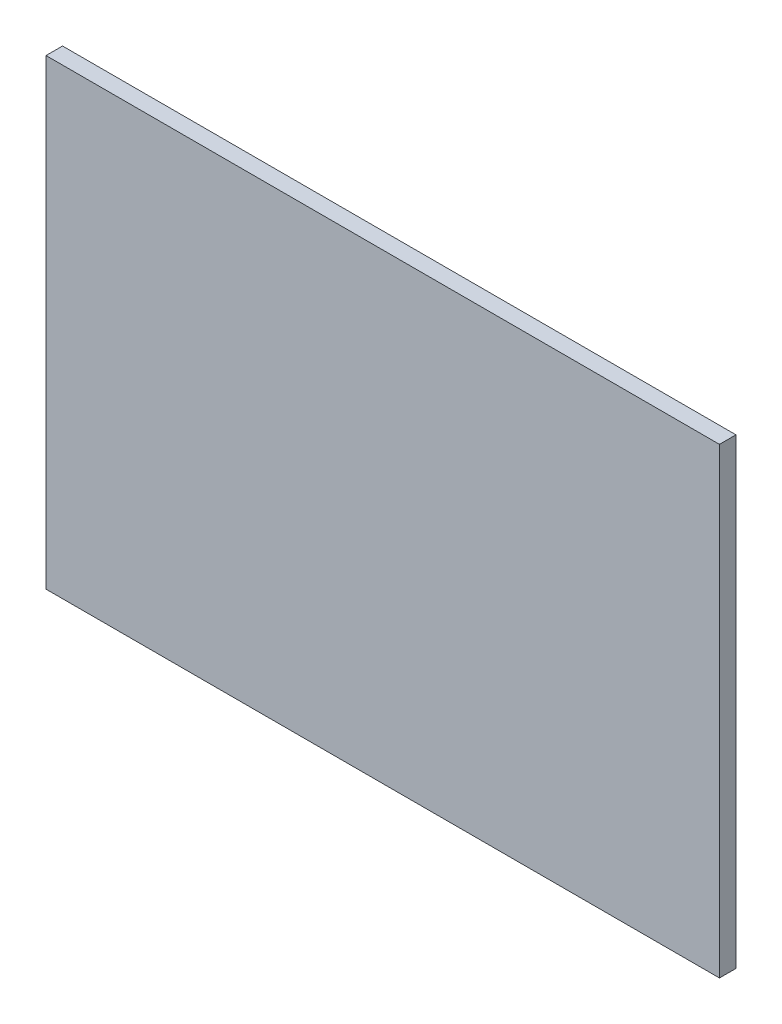
SolidWorks part; units mm, degrees
ref_plane "Спереди" through (0, 0, 0) normal (0, 0, 1) x (1, 0, 0)
ref_plane "Сверху" through (0, 0, 0) normal (0, 1, 0) x (1, 0, 0)
ref_plane "Справа" through (0, 0, 0) normal (1, 0, 0) x (0, 0, -1)
sketch "Эскиз1" plane through (0, 0, 0) normal (0, 0, 1) x (1, 0, 0)
  line L1 (-30.6, 21) -> (30.6, 21)
  line L2 (-30.6, 21) -> (-30.6, -21)
  line L3 (-30.6, -21) -> (30.6, -21)
  line L4 (30.6, 21) -> (30.6, -21)
  line L5 (-30.6, 21) -> (30.6, -21) construction
  line L6 (-30.6, -21) -> (30.6, 21) construction
  point P0 (0, 0)
  dimension "D1" = 42
  dimension "D2" = 61.2
extrude "Бобышка-Вытянуть1" add sketch "Эскиз1" along normal blind 1.5
